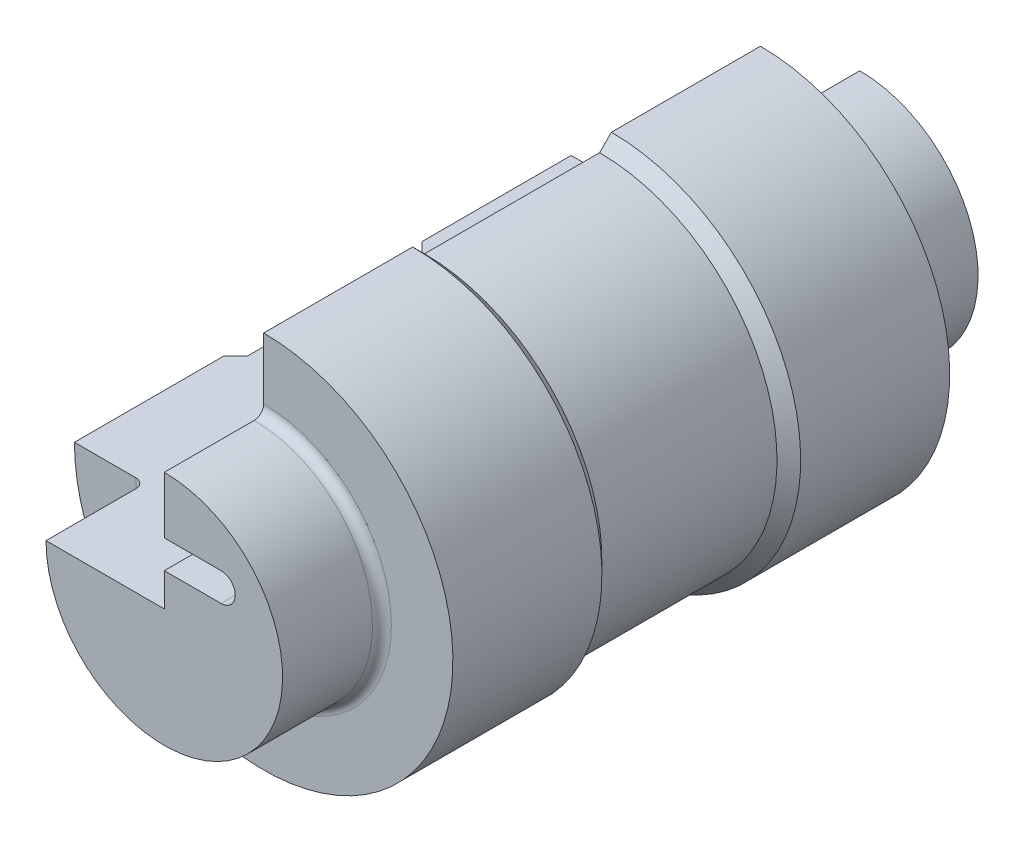
SolidWorks part; units mm, degrees
material "AISI 1020"
ref_plane "Plan de face" through (0, 0, 0) normal (0, 0, 1) x (1, 0, 0)
ref_plane "Plan de dessus" through (0, 0, 0) normal (0, 1, 0) x (1, 0, 0)
ref_plane "Plan de droite" through (0, 0, 0) normal (1, 0, 0) x (0, 0, -1)
sketch "Esquisse1" plane through (0, 0, 0) normal (1, 0, 0) x (0, 0, -1)
  line L0 (-73.5, 0) -> (73.5, 0)
  line L1 (55, 0) -> (-55, 0) construction
  line L2 (73.5, 0) -> (73.5, 25)
  line L3 (73.5, 25) -> (54.5, 25)
  line L4 (52.5, 27) -> (52.5, 40)
  line L5 (52.5, 40) -> (21, 40)
  line L6 (21, 40) -> (18.5, 37.5)
  line L7 (18.5, 37.5) -> (-18.5, 37.5)
  line L8 (0, 55) -> (0, -55) construction
  line L9 (-21, 40) -> (-18.5, 37.5)
  line L10 (-52.5, 40) -> (-21, 40)
  line L11 (-52.5, 27) -> (-52.5, 40)
  line L12 (-73.5, 25) -> (-54.5, 25)
  line L13 (-73.5, 0) -> (-73.5, 25)
  arc A0 (54.5, 25) -> (52.5, 27) centre (54.5, 27) cw
  arc A1 (-52.5, 27) -> (-54.5, 25) centre (-54.5, 27) cw
  point P0 (0, 0)
  point P14 (0, 37.5)
  point P19 (0, 0)
  point P22 (52.5, 25)
  point P25 (-52.5, 25)
  dimension "D6" = 2
  dimension "D7" = 2
  dimension "D1" = 25
  dimension "D2" = 40
  dimension "D3" = 21
  dimension "D4" = 31.5
  dimension "D5" = 147
  dimension "D8" = 2.5
  dimension "D9" = 135
revolve "Révolution1" add sketch "Esquisse1" angle 360 about L0
sketch "Esquisse3" plane through (0, 0, 0) normal (0, 0, 1) x (1, 0, 0)
  line L1 (0, 0) -> (-49.5903, 0)
  line L2 (0, 0) -> (0, 55.3279)
  line L3 (0, 55.3279) -> (-49.5903, 55.3279)
  line L4 (-49.5903, 0) -> (-49.5903, 55.3279)
extrude "Enlèv. mat.-Extru.1" cut sketch "Esquisse3" against normal through all both and the other way through all
sketch "Esquisse4" plane through (0, 0, 0) normal (0, 0, 1) x (1, 0, 0)
  line L0 (0, 0) -> (0, 7)
  line L1 (0, -52.4303) -> (0, 52.4303) construction
  line L2 (0, 7) -> (12, 7)
  line L3 (12, 13) -> (0, 13)
  line L4 (49.2747, 0) -> (-49.2747, 0) construction
  line L5 (0, 13) -> (0, 7)
  arc A0 (12, 7) -> (12, 13) centre (12, 10) ccw
  dimension "D3" = 3
  dimension "D1" = 12
  dimension "D2" = 7
extrude "Enlèv. mat.-Extru.2" cut sketch "Esquisse4" against normal through all both and the other way through all contours L2 A0 L3 L5
equation "\"A\"= 147"
equation "\"B\"= 21"
equation "\"C\"= 31.5"
equation "\"D3@Esquisse1\"=\"B\""
equation "\"D4@Esquisse1\"=\"C\""
equation "\"D5@Esquisse1\"=\"A\""
